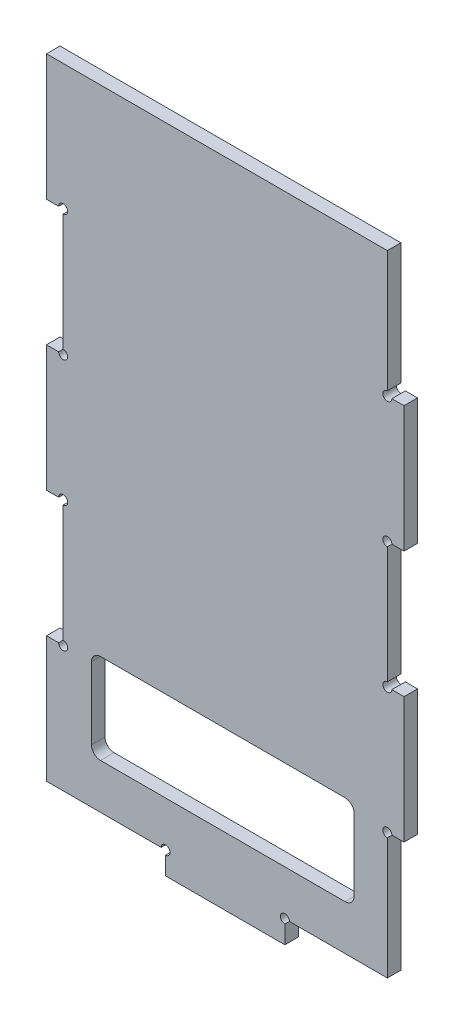
SolidWorks part; units mm, degrees
material "Alumina"
ref_plane "Front Plane" through (0, 0, 0) normal (0, 0, 1) x (1, 0, 0)
ref_plane "Top Plane" through (0, 0, 0) normal (0, 1, 0) x (1, 0, 0)
ref_plane "Right Plane" through (0, 0, 0) normal (1, 0, 0) x (0, 0, -1)
sketch "Sketch1" plane through (0, 0, 0) normal (0, 0, 1) x (1, 0, 0)
  line L1 (-39.725, -70) -> (39.725, -70)
  line L2 (-39.725, -70) -> (-39.725, 70)
  line L3 (-39.725, 70) -> (39.725, 70)
  line L4 (39.725, -70) -> (39.725, 70)
  line L5 (-39.725, -70) -> (39.725, 70) construction
  line L6 (-39.725, 70) -> (39.725, -70) construction
  point P0 (0, 0)
extrude "Boss-Extrude1" add sketch "Sketch1" along normal blind 3
sketch "Sketch2" plane through (0, 0, 3) normal (0, 0, 1) x (1, 0, 0)
  line L0 (-39.725, -70) -> (39.725, -70) construction
  line L1 (-29.725, -60) -> (28.625, -60)
  line L2 (-29.725, -60) -> (-29.725, -40)
  line L3 (-29.725, -40) -> (28.625, -40)
  line L4 (28.625, -60) -> (28.625, -40)
  line L5 (-29.725, -60) -> (28.625, -40) construction
  line L6 (-29.725, -40) -> (28.625, -60) construction
  line L7 (-39.725, 70) -> (-39.725, -70) construction
  point P0 (-0.55, -50)
  dimension "D1" = 10
  dimension "D2" = 10
extrude "Cut-Extrude1" cut sketch "Sketch2" against normal through all
fillet "Fillet1" radius 2 4 edges at (28.625, -60, 1.5) (28.625, -40, 1.5) (-29.725, -60, 1.5) (-29.725, -40, 1.5)
sketch "Sketch3" plane through (0, 0, 3) normal (0, 0, 1) x (1, 0, 0)
  line L0 (-39.725, 70) -> (-39.725, -70) construction
  line L1 (-39.725, 42) -> (-36.025, 42)
  line L2 (-39.725, 42) -> (-39.725, 14)
  line L3 (-39.725, 14) -> (-36.025, 14)
  line L4 (-36.025, 42) -> (-36.025, 14)
  line L5 (39.725, -70) -> (39.725, 70) construction
  line L6 (-39.725, -42) -> (-36.025, -42)
  line L7 (-39.725, -42) -> (-39.725, -14)
  line L8 (-39.725, -14) -> (-36.025, -14)
  line L9 (-36.025, -42) -> (-36.025, -14)
  line L10 (39.725, 70) -> (36.025, 70)
  line L11 (39.725, 70) -> (39.725, 42)
  line L12 (39.725, 42) -> (36.025, 42)
  line L13 (36.025, 70) -> (36.025, 42)
  line L14 (39.725, 14) -> (36.025, 14)
  line L15 (39.725, 14) -> (39.725, -14)
  line L16 (39.725, -14) -> (36.025, -14)
  line L17 (36.025, 14) -> (36.025, -14)
  line L19 (39.725, -70) -> (36.025, -70)
  line L20 (39.725, -70) -> (39.725, -42)
  line L21 (39.725, -42) -> (36.025, -42)
  line L22 (36.025, -70) -> (36.025, -42)
  dimension "D1" = 28
  dimension "D2" = 28
extrude "Cut-Extrude2" cut sketch "Sketch3" against normal through all
sketch "Sketch5" plane through (0, 0, 3) normal (0, 0, 1) x (1, 0, 0)
  line L0 (-39.725, -70) -> (36.025, -70) construction
  line L1 (-13.25, -75) -> (13.25, -75)
  line L2 (-13.25, -75) -> (-13.25, -70)
  line L3 (-13.25, -70) -> (13.25, -70)
  line L4 (13.25, -75) -> (13.25, -70)
  line L5 (-13.25, -75) -> (13.25, -70) construction
  line L6 (-13.25, -70) -> (13.25, -75) construction
  point P0 (0, -72.5)
extrude "Boss-Extrude2" add sketch "Sketch5" against normal blind 3
sketch "Sketch6" plane through (0, 0, 3) normal (0, 0, 1) x (1, 0, 0)
  circle A0 centre (-36.025, 42) radius 1
  circle A1 centre (-36.025, 14) radius 1
  circle A2 centre (-36.025, -14) radius 1
  circle A3 centre (-36.025, -42) radius 1
  circle A4 centre (-13.25, -70) radius 1
  circle A5 centre (13.25, -70) radius 1
  circle A6 centre (36.025, -42) radius 1
  circle A7 centre (36.025, -14) radius 1
  circle A8 centre (36.025, 14) radius 1
  circle A9 centre (36.025, 42) radius 1
extrude "Cut-Extrude3" cut sketch "Sketch6" against normal through all
